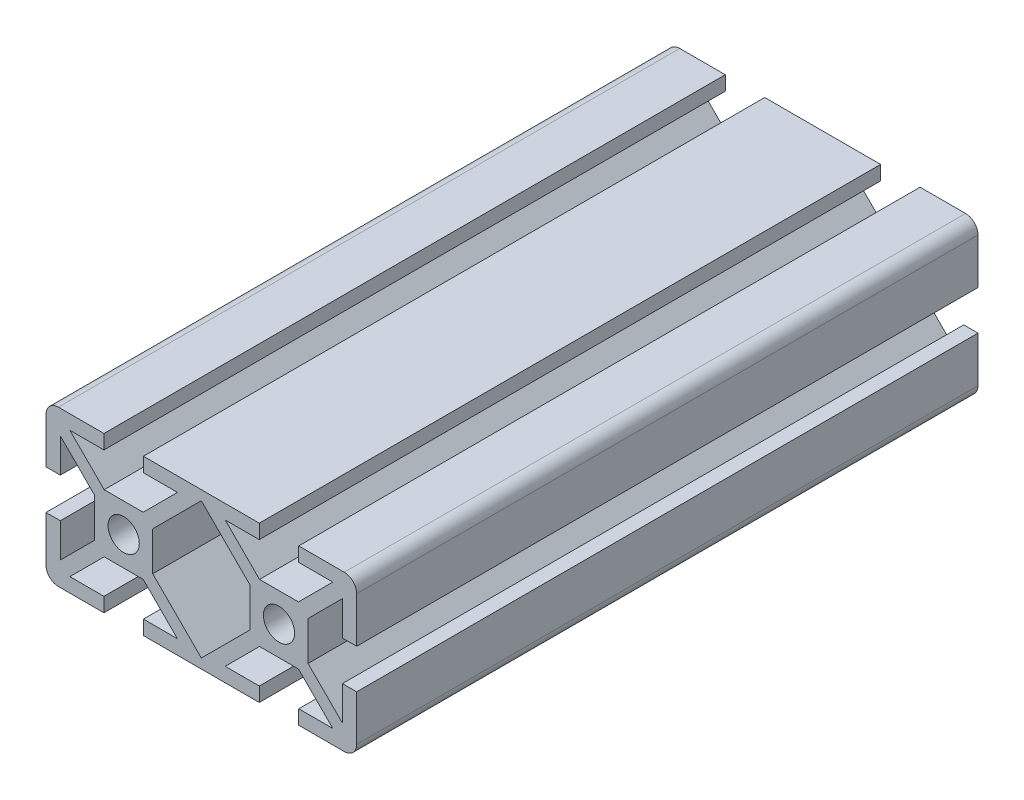
SolidWorks part; units mm, degrees
ref_plane "Front"
ref_plane "Top" through (0, 0, 0) normal (0, 1, 0) x (1, 0, 0)
ref_plane "Right" through (0, 0, 0) normal (1, 0, 0) x (0, 0, -1)
sketch "Sketch1" plane through (0, 0, 0) normal (0, 0, 1) x (1, 0, 0)
  line L0 (-12.7, 0) -> (-12.7, 36.1419) construction
  line L1 (-12.7, 0) -> (-38.1248, 0) construction
  line L2 (-17.4498, 0) -> (-17.4498, 3.1872)
  line L3 (-17.4498, 3.1872) -> (-23.0632, 8.8006)
  line L4 (-23.0632, 3.2258) -> (-23.0632, 8.8006)
  line L5 (-23.368, 12.7) -> (-15.9258, 12.7)
  line L6 (-25.4, 3.2258) -> (-25.4, 10.668)
  line L7 (-12.7, 4.7498) -> (-15.8872, 4.7498)
  line L8 (-15.8872, 4.7498) -> (-21.5006, 10.3632)
  line L9 (-21.5006, 10.3632) -> (-15.9258, 10.3632)
  line L10 (-9.5128, 4.7498) -> (-3.8994, 10.3632)
  line L11 (-3.8994, 10.3632) -> (-9.4742, 10.3632)
  line L12 (-15.9258, 12.7) -> (-15.9258, 10.3632)
  line L13 (9.4742, 12.7) -> (-9.4742, 12.7)
  line L14 (7.9502, 3.1872) -> (0, 11.1374)
  line L15 (-7.9502, 3.1872) -> (0, 11.1374)
  line L16 (-12.7, 4.7498) -> (-9.5128, 4.7498)
  line L17 (-7.9502, 3.1872) -> (-7.9502, 0)
  line L18 (-12.7, -4.7498) -> (-9.5128, -4.7498)
  line L19 (-7.9502, -3.1872) -> (0, -11.1374)
  line L20 (9.5128, 4.7498) -> (3.8994, 10.3632)
  line L21 (-9.5128, -4.7498) -> (-3.8994, -10.3632)
  line L22 (3.8994, 10.3632) -> (9.4742, 10.3632)
  line L23 (-3.8994, -10.3632) -> (-9.4742, -10.3632)
  line L24 (-9.4742, -12.7) -> (-9.4742, -10.3632)
  line L25 (-23.0632, -3.2258) -> (-25.4, -3.2258)
  line L26 (-23.0632, -3.2258) -> (-23.0632, -8.8006)
  line L27 (-12.7, -4.7498) -> (-15.8872, -4.7498)
  line L28 (-25.4, -3.2258) -> (-25.4, -10.668)
  line L29 (-23.368, -12.7) -> (-15.9258, -12.7)
  line L30 (-17.4498, -3.1872) -> (-23.0632, -8.8006)
  line L31 (-15.8872, -4.7498) -> (-21.5006, -10.3632)
  line L32 (-7.9502, 0) -> (-7.9502, -3.1872)
  line L33 (-17.4498, 0) -> (-17.4498, -3.1872)
  line L34 (0, 23.5779) -> (0, -24.9502) construction
  line L35 (9.4742, 12.7) -> (9.4742, 10.3632)
  line L36 (7.9502, 0) -> (7.9502, -3.1872)
  line L37 (7.9502, 3.1872) -> (7.9502, 0)
  line L38 (23.0632, 3.2258) -> (25.4, 3.2258)
  line L39 (15.9258, 12.7) -> (15.9258, 10.3632)
  line L40 (21.5006, 10.3632) -> (15.9258, 10.3632)
  line L41 (15.8872, 4.7498) -> (21.5006, 10.3632)
  line L42 (17.4498, 0) -> (17.4498, -3.1872)
  line L43 (25.4, 3.2258) -> (25.4, 10.668)
  line L44 (23.368, 12.7) -> (15.9258, 12.7)
  line L45 (23.0632, 3.2258) -> (23.0632, 8.8006)
  line L46 (17.4498, 3.1872) -> (23.0632, 8.8006)
  line L47 (12.7, -4.7498) -> (15.8872, -4.7498)
  line L48 (15.9258, -12.7) -> (15.9258, -10.3632)
  line L49 (21.5006, -10.3632) -> (15.9258, -10.3632)
  line L50 (12.7, -4.7498) -> (9.5128, -4.7498)
  line L51 (15.8872, 4.7498) -> (9.5128, 4.7498)
  line L52 (15.8872, -4.7498) -> (21.5006, -10.3632)
  line L53 (17.4498, -3.1872) -> (23.0632, -8.8006)
  line L54 (23.368, -12.7) -> (15.9258, -12.7)
  line L55 (25.4, -3.2258) -> (25.4, -10.668)
  line L56 (23.0632, -3.2258) -> (23.0632, -8.8006)
  line L57 (23.0632, -3.2258) -> (25.4, -3.2258)
  line L58 (9.4742, -12.7) -> (9.4742, -10.3632)
  line L59 (17.4498, 0) -> (17.4498, 3.1872)
  line L60 (-23.0632, 3.2258) -> (-25.4, 3.2258)
  line L61 (-9.4742, 12.7) -> (-9.4742, 10.3632)
  line L62 (-21.5006, -10.3632) -> (-15.9258, -10.3632)
  line L63 (-15.9258, -12.7) -> (-15.9258, -10.3632)
  line L64 (9.4742, -12.7) -> (-9.4742, -12.7)
  line L65 (3.8994, -10.3632) -> (9.4742, -10.3632)
  line L66 (9.5128, -4.7498) -> (3.8994, -10.3632)
  line L67 (7.9502, -3.1872) -> (0, -11.1374)
  arc A0 (-23.368, 12.7) -> (-25.4, 10.668) centre (-23.368, 10.668) ccw
  arc A1 (23.368, 12.7) -> (25.4, 10.668) centre (23.368, 10.668) cw
  arc A2 (23.368, -12.7) -> (25.4, -10.668) centre (23.368, -10.668) ccw
  arc A19 (-23.368, -12.7) -> (-25.4, -10.668) centre (-23.368, -10.668) cw
  circle A20 centre (-12.7, 0) radius 2.5527
  circle A23 centre (12.7, 0) radius 2.5527
  point P34 (0, 12.7)
  point P51 (0, -12.7)
  dimension "D2" = 12.7
  dimension "D5" = 2.2098
  dimension "D6" = 7.9502
  dimension "D4" = 9.4742
  dimension "D11" = 5.1054
  dimension "D12" = 12.7
  dimension "D3" = 2.032
  dimension "D1" = 12.7
  dimension "D7" = 7.9502
  dimension "D8" = 45
  dimension "D9" = 5.6134
  dimension "D10" = 5.6134
extrude "FinalCut" add sketch "Sketch1" against normal blind 101.6
ref_plane "A" through (0, 0, 0) normal (0, 0, 1) x (1, 0, 0)
ref_plane "B" through (0, 0, -101.6) normal (0, 0, -1) x (-1, 0, 0)
ref_plane "Y+" through (0, 12.7, 0) normal (0, 1, 0) x (-1, 0, 0)
ref_plane "X+" through (25.4, 0, 0) normal (1, 0, 0) x (0, 0, -1)
ref_plane "Y-" through (0, -12.7, 0) normal (0, -1, 0) x (1, 0, 0)
ref_plane "X-" through (-25.4, 0, 0) normal (-1, 0, 0) x (0, 0, 1)
ref_plane "Slot-3-6-" through (0, 0, 0) normal (0, 1, 0) x (0, 0, -1)
ref_plane "Slot-1-5-" through (-12.7, 0, 0) normal (1, 0, 0) x (0, 1, 0)
ref_plane "Slot-2-4-" through (12.7, 0, 0) normal (1, 0, 0) x (0, 1, 0)
sketch "Sketch3" plane through (0, 12.7, 0) normal (0, 1, 0) x (-1, 0, 0)
  line L0 (12.7, 0) -> (12.7, -31.4571) construction
  line L1 (9.5128, 0) -> (15.8872, 0) construction
  line L2 (15.9258, 0) -> (23.368, 0) construction
  circle A0 centre (12.7, -10.3124) radius 7.1501
  dimension "D2" = 14.3002
  dimension "D1" = 12.7
  dimension "D3" = 10.3124
extrude "AFA1" [suppressed] cut sketch "Sketch3" against normal blind 10.668
sketch "Sketch2" plane through (0, 12.7, 0) normal (0, 1, 0) x (-1, 0, 0)
  line L0 (-12.7, 0.1154) -> (-12.7, -30.7514) construction
  line L2 (-15.8872, 0) -> (-9.5128, 0) construction
  circle A0 centre (-12.7, -10.3124) radius 7.1501
  dimension "D2" = 14.3002
  dimension "D1" = 12.7
  dimension "D3" = 10.3124
extrude "AFA2" [suppressed] cut sketch "Sketch2" against normal blind 10.668
sketch "Sketch4" plane through (25.4, 0, 0) normal (1, 0, 0) x (0, 0, -1)
  line L0 (0, 0) -> (26.9656, 0) construction
  line L1 (0, -3.1872) -> (0, 3.1872) construction
  circle A0 centre (10.3124, 0) radius 7.1501
  dimension "D1" = 14.3002
  dimension "D2" = 10.3124
extrude "AFA3" [suppressed] cut sketch "Sketch4" against normal blind 10.668
sketch "Sketch5" plane through (0, -12.7, 0) normal (0, -1, 0) x (1, 0, 0)
  line L0 (12.7, 0) -> (12.7, -32.6419) construction
  line L1 (9.5128, 0) -> (15.8872, 0) construction
  circle A0 centre (12.7, -10.3124) radius 7.1501
  dimension "D2" = 14.3002
  dimension "D1" = 12.7
  dimension "D3" = 10.3124
extrude "AFA4" [suppressed] cut sketch "Sketch5" against normal blind 10.668
sketch "Sketch6" plane through (0, -12.7, 0) normal (0, -1, 0) x (1, 0, 0)
  line L0 (-12.7, 0) -> (-12.7, -32.1497) construction
  line L1 (-15.8872, 0) -> (-9.5128, 0) construction
  line L2 (-9.4742, 0) -> (9.4742, 0) construction
  circle A0 centre (-12.7, -10.3124) radius 7.1501
  dimension "D2" = 14.3002
  dimension "D1" = 12.7
  dimension "D3" = 10.3124
extrude "AFA5" [suppressed] cut sketch "Sketch6" against normal blind 10.668
sketch "Sketch7" plane through (-25.4, 0, 0) normal (-1, 0, 0) x (0, 0, 1)
  line L0 (0, 0) -> (-27.1523, 0) construction
  line L1 (0, 3.1872) -> (0, -3.1872) construction
  circle A0 centre (-10.3124, 0) radius 7.1501
  dimension "D1" = 14.3002
  dimension "D2" = 10.3124
extrude "AFA6" [suppressed] cut sketch "Sketch7" against normal blind 10.668
sketch "Sketch8" plane through (0, 12.7, 0) normal (0, 1, 0) x (-1, 0, 0)
  line L0 (12.7, -101.6) -> (12.7, 6.9228) construction
  line L1 (9.5128, -101.6) -> (15.8872, -101.6) construction
  circle A0 centre (12.7, -91.2876) radius 7.1501
  dimension "D1" = 14.3002
  dimension "D2" = 10.3124
  dimension "D3" = 12.7
extrude "AFB1" [suppressed] cut sketch "Sketch8" against normal blind 10.668
sketch "Sketch9" plane through (0, 12.7, 0) normal (0, 1, 0) x (-1, 0, 0)
  line L0 (-12.7, -17.9733) -> (-12.7, 12.1535) construction
  line L1 (-15.8872, -101.6) -> (-9.5128, -101.6) construction
  circle A0 centre (-12.7, -91.2876) radius 7.1501
  dimension "D1" = 14.3002
  dimension "D2" = 10.3124
  dimension "D3" = 12.7
extrude "AFB2" [suppressed] cut sketch "Sketch9" against normal blind 10.668
sketch "Sketch10" plane through (25.4, 0, 0) normal (1, 0, 0) x (0, 0, -1)
  line L0 (0, 0) -> (101.6, 0) construction
  line L1 (101.6, -3.1872) -> (101.6, 3.1872) construction
  circle A0 centre (91.2876, 0) radius 7.1501
  dimension "D1" = 14.3002
  dimension "D2" = 10.3124
extrude "AFB3" [suppressed] cut sketch "Sketch10" against normal blind 10.668
sketch "Sketch11" plane through (0, -12.7, 0) normal (0, -1, 0) x (1, 0, 0)
  line L0 (12.7, 0) -> (12.7, -101.6) construction
  line L1 (9.5128, 0) -> (15.8872, 0) construction
  line L2 (9.5128, -101.6) -> (15.8872, -101.6) construction
  line L3 (-9.4742, -101.6) -> (9.4742, -101.6) construction
  circle A0 centre (12.7, -91.2876) radius 7.1501
  dimension "D2" = 14.3002
  dimension "D1" = 12.7
  dimension "D3" = 10.3124
extrude "AFB4" [suppressed] cut sketch "Sketch11" against normal blind 10.668
sketch "Sketch12" plane through (0, -12.7, 0) normal (0, -1, 0) x (1, 0, 0)
  line L0 (-12.7, -101.6) -> (-12.7, 0) construction
  line L1 (-15.8872, -101.6) -> (-9.5128, -101.6) construction
  line L2 (-15.8872, 0) -> (-9.5128, 0) construction
  line L3 (-9.4742, -101.6) -> (9.4742, -101.6) construction
  circle A0 centre (-12.7, -91.2876) radius 7.1501
  dimension "D2" = 14.3002
  dimension "D1" = 12.7
  dimension "D3" = 10.3124
extrude "AFB5" [suppressed] cut sketch "Sketch12" against normal blind 10.668
sketch "Sketch13" plane through (-25.4, 0, 0) normal (-1, 0, 0) x (0, 0, 1)
  line L0 (0, 0) -> (-101.6, 0) construction
  line L1 (-101.6, 3.1872) -> (-101.6, -3.1872) construction
  line L2 (-101.6, -3.2258) -> (-101.6, -10.668) construction
  circle A0 centre (-91.2876, 0) radius 7.1501
  dimension "D1" = 14.3002
  dimension "D2" = 10.3124
extrude "AFB6" [suppressed] cut sketch "Sketch13" against normal blind 10.668
sketch "Sketch14" plane through (0, 0, -101.6) normal (0, 0, -1) x (-1, 0, 0)
  point P0 (0, 0)
sketch "Sketch15" plane through (0, 0, 0) normal (0, 0, 1) x (1, 0, 0)
  circle A0 centre (-12.7, 0) radius 3.302
  circle A1 centre (12.7, 0) radius 3.302
  dimension "D1" = 6.604
extrude "TPA660025" [suppressed] cut sketch "Sketch15" against normal blind 19.05
sketch "Sketch16" plane through (0, 0, -101.6) normal (0, 0, -1) x (-1, 0, 0)
  circle A0 centre (12.7, 0) radius 3.302
  circle A1 centre (-12.7, 0) radius 3.302
  dimension "D1" = 6.604
extrude "TPB660025" [suppressed] cut sketch "Sketch16" against normal blind 19.05
sketch "Sketch17" plane through (0, 0, 0) normal (0, 0, 1) x (1, 0, 0)
  circle A0 centre (-12.7, 0) radius 3.175
  circle A1 centre (12.7, 0) radius 3.175
  dimension "D1" = 6.35
extrude "TPA660026" [suppressed] cut sketch "Sketch17" against normal blind 25.4
sketch "Sketch18" plane through (0, 0, -101.6) normal (0, 0, -1) x (-1, 0, 0)
  circle A0 centre (12.7, 0) radius 3.175
  circle A1 centre (-12.7, 0) radius 3.175
  dimension "D1" = 6.35
extrude "TPB660026" [suppressed] cut sketch "Sketch18" against normal blind 25.4
sketch "Sketch19" plane through (0, 0, 0) normal (1, 0, 0) x (0, 0, -1)
  line L0 (0, 12.7) -> (25.4, -12.7)
  line L1 (101.6, 12.7) -> (0, 12.7) construction
  line L2 (101.6, -12.7) -> (0, -12.7) construction
  dimension "D1" = 45
extrude "MITA1" [suppressed] cut sketch "Sketch19" against normal through all and the other way through all flip side to cut
ref_plane "AMITA1" [suppressed] through (0, 6.35, -6.35) normal (0, 0.7071, -0.7071) x (-1, 0, 0)
ref_plane "AMIT0FFA1" [suppressed] through (0, 10.8401, -10.8401) normal (0, 0.7071, -0.7071) x (-1, 0, 0)
sketch "Sketch23" [suppressed] plane through (0, 10.8401, -10.8401) normal (0, 0.7071, -0.7071) x (-1, 0, 0)
  line L0 (-9.4742, 8.9803) -> (9.4742, 8.9803) construction
  circle A0 centre (-12.7, -8.9775) radius 7.9375
  circle A1 centre (12.7, -8.9775) radius 7.9375
  dimension "D1" = 25.4
  dimension "D2" = 15.875
  dimension "D3" = 12.7
  dimension "D4" = 17.9578
extrude "MITCBA1" [suppressed] cut sketch "Sketch23" along normal through all
sketch "Sketch24" [suppressed] plane through (0, 10.8401, -10.8401) normal (0, 0.7071, -0.7071) x (-1, 0, 0)
  line L1 (-9.4742, 8.9803) -> (9.4742, 8.9803) construction
  circle A0 centre (-12.7, -8.9775) radius 3.2639
  circle A1 centre (12.7, -8.9775) radius 3.2639
  dimension "D1" = 6.5278
  dimension "D2" = 25.4
  dimension "D3" = 12.7
  dimension "D4" = 17.9578
extrude "MITDRA1" [suppressed] cut sketch "Sketch24" against normal through all
sketch "Sketch25" [suppressed] plane through (0, 10.8401, -10.8401) normal (0, 0.7071, -0.7071) x (-1, 0, 0)
  line L0 (-20.6375, -8.9775) -> (-20.6375, 8.9803)
  line L1 (-4.7625, -8.9775) -> (-4.7625, 8.9803)
  line L2 (-4.7625, 8.9803) -> (-20.6375, 8.9803)
  line L3 (4.7625, 8.9803) -> (4.7625, -8.9775)
  line L4 (20.6375, -8.9775) -> (20.6375, 8.9803)
  line L5 (20.6375, 8.9803) -> (4.7625, 8.9803)
  line L6 (-9.4742, 8.9803) -> (9.4742, 8.9803) construction
  arc A0 (-20.6375, -8.9775) -> (-4.7625, -8.9775) centre (-12.7, -8.9775) ccw
  arc A1 (4.7625, -8.9775) -> (20.6375, -8.9775) centre (12.7, -8.9775) ccw
  dimension "D1" = 7.9375
  dimension "D3" = 25.4
  dimension "D4" = 12.7
  dimension "D2" = 17.9578
extrude "MITEBA1" [suppressed] cut sketch "Sketch25" along normal through all
sketch "Sketch26" [suppressed] plane through (0, 10.8401, -10.8401) normal (0, 0.7071, -0.7071) x (-1, 0, 0)
  line L0 (-15.9639, 8.9803) -> (-9.4361, 8.9803)
  line L1 (-9.4361, 8.9803) -> (-9.4361, -8.9775)
  line L2 (-15.9639, -8.9775) -> (-15.9639, 8.9803)
  line L3 (9.4361, 8.9803) -> (9.4361, -8.9775)
  line L4 (15.9639, -8.9775) -> (15.9639, 8.9803)
  line L5 (15.9639, 8.9803) -> (9.4361, 8.9803)
  line L6 (-9.4742, 8.9803) -> (9.4742, 8.9803) construction
  arc A0 (-9.4361, -8.9775) -> (-15.9639, -8.9775) centre (-12.7, -8.9775) cw
  arc A1 (9.4361, -8.9775) -> (15.9639, -8.9775) centre (12.7, -8.9775) ccw
  dimension "D1" = 3.2639
  dimension "D2" = 17.9578
  dimension "D3" = 25.4
  dimension "D4" = 12.7
extrude "MITEDA1" [suppressed] cut sketch "Sketch26" against normal through all
sketch "Sketch20" plane through (0, 0, 0) normal (1, 0, 0) x (0, 0, -1)
  line L0 (101.6, 12.7) -> (76.2, -12.7)
  line L1 (101.6, 12.7) -> (0, 12.7) construction
  line L2 (101.6, -12.7) -> (0, -12.7) construction
  dimension "D1" = 45
extrude "MITB1" [suppressed] cut sketch "Sketch20" against normal through all and the other way through all
ref_plane "AMITB1" [suppressed] through (0, -44.45, -44.45) normal (0, 0.7071, 0.7071) x (1, 0, 0)
ref_plane "AMITOFFB1" [suppressed] through (0, -39.9599, -39.9599) normal (0, 0.7071, 0.7071) x (1, 0, 0)
sketch "Sketch27" [suppressed] plane through (0, -39.9599, -39.9599) normal (0, 0.7071, 0.7071) x (1, 0, 0)
  line L1 (9.4742, 80.8223) -> (-9.4742, 80.8223) construction
  circle A0 centre (-12.7, 62.8645) radius 7.9375
  circle A1 centre (12.7, 62.8645) radius 7.9375
  dimension "D1" = 15.875
  dimension "D2" = 25.4
  dimension "D3" = 12.7
  dimension "D4" = 17.9578
extrude "MITCBB1" [suppressed] cut sketch "Sketch27" along normal through all
sketch "Sketch28" [suppressed] plane through (0, -39.9599, -39.9599) normal (0, 0.7071, 0.7071) x (1, 0, 0)
  line L0 (9.4742, 80.8223) -> (-9.4742, 80.8223) construction
  circle A0 centre (-12.7, 62.8645) radius 3.2639
  circle A1 centre (12.7, 62.8645) radius 3.2639
  dimension "D1" = 25.4
  dimension "D2" = 12.7
  dimension "D3" = 6.5278
  dimension "D4" = 17.9578
extrude "MITDRB1" [suppressed] cut sketch "Sketch28" against normal through all
sketch "Sketch29" [suppressed] plane through (0, -39.9599, -39.9599) normal (0, 0.7071, 0.7071) x (1, 0, 0)
  line L0 (-20.6375, 80.8223) -> (-20.6375, 62.8645)
  line L1 (-4.7625, 62.8645) -> (-4.7625, 80.8223)
  line L2 (-4.7625, 80.8223) -> (-20.6375, 80.8223)
  line L3 (4.7625, 80.8223) -> (4.7625, 62.8645)
  line L4 (20.6375, 62.8645) -> (20.6375, 80.8223)
  line L5 (20.6375, 80.8223) -> (4.7625, 80.8223)
  line L8 (9.4742, 80.8223) -> (-9.4742, 80.8223) construction
  arc A0 (-20.6375, 62.8645) -> (-4.7625, 62.8645) centre (-12.7, 62.8645) ccw
  arc A1 (4.7625, 62.8645) -> (20.6375, 62.8645) centre (12.7, 62.8645) ccw
  dimension "D1" = 25.4
  dimension "D2" = 12.7
  dimension "D3" = 7.9375
  dimension "D4" = 17.9578
extrude "MITEBB1" [suppressed] cut sketch "Sketch29" along normal through all
sketch "Sketch30" [suppressed] plane through (0, -39.9599, -39.9599) normal (0, 0.7071, 0.7071) x (1, 0, 0)
  line L0 (-15.9639, 80.8223) -> (-15.9639, 62.8645)
  line L1 (-9.4361, 62.8645) -> (-9.4361, 80.8223)
  line L2 (-9.4361, 80.8223) -> (-15.9639, 80.8223)
  line L3 (9.4361, 80.8223) -> (9.4361, 62.8645)
  line L4 (15.9639, 62.8645) -> (15.9639, 80.8223)
  line L5 (15.9639, 80.8223) -> (9.4361, 80.8223)
  line L6 (9.4742, 80.8223) -> (-9.4742, 80.8223) construction
  arc A0 (-15.9639, 62.8645) -> (-9.4361, 62.8645) centre (-12.7, 62.8645) ccw
  arc A1 (9.4361, 62.8645) -> (15.9639, 62.8645) centre (12.7, 62.8645) ccw
  dimension "D1" = 17.9578
  dimension "D2" = 3.2639
  dimension "D3" = 25.4
  dimension "D4" = 12.7
extrude "MITEDB1" [suppressed] cut sketch "Sketch30" against normal through all
sketch "Sketch21" plane through (0, 0, 0) normal (1, 0, 0) x (0, 0, -1)
  line L0 (0, -12.7) -> (25.4, 12.7)
  line L1 (101.6, -12.7) -> (0, -12.7) construction
  line L2 (101.6, 12.7) -> (0, 12.7) construction
  dimension "D1" = 45
extrude "MITA4" [suppressed] cut sketch "Sketch21" against normal through all and the other way through all
ref_plane "AMITA4" [suppressed] through (0, -6.35, -6.35) normal (0, -0.7071, -0.7071) x (-1, 0, 0)
ref_plane "AMITOFFA4" [suppressed] through (0, -10.8401, -10.8401) normal (0, -0.7071, -0.7071) x (-1, 0, 0)
sketch "Sketch31" [suppressed] plane through (0, -10.8401, -10.8401) normal (0, -0.7071, -0.7071) x (-1, 0, 0)
  line L0 (9.4742, -8.9803) -> (-9.4742, -8.9803) construction
  circle A0 centre (-12.7, 8.9775) radius 7.9375
  circle A1 centre (12.7, 8.9775) radius 7.9375
  dimension "D1" = 15.875
  dimension "D2" = 12.7
  dimension "D3" = 25.4
  dimension "D4" = 17.9578
extrude "MITCBA4" [suppressed] cut sketch "Sketch31" along normal through all
sketch "Sketch32" [suppressed] plane through (0, -10.8401, -10.8401) normal (0, -0.7071, -0.7071) x (-1, 0, 0)
  line L0 (9.4742, -8.9803) -> (-9.4742, -8.9803) construction
  circle A0 centre (-12.7, 8.9775) radius 3.2639
  circle A1 centre (12.7, 8.9775) radius 3.2639
  dimension "D1" = 6.5278
  dimension "D2" = 17.9578
  dimension "D3" = 25.4
  dimension "D4" = 12.7
extrude "MITDRA4" [suppressed] cut sketch "Sketch32" against normal through all
sketch "Sketch33" [suppressed] plane through (0, -10.8401, -10.8401) normal (0, -0.7071, -0.7071) x (-1, 0, 0)
  line L0 (-20.6375, -8.9803) -> (-4.7625, -8.9803)
  line L1 (-4.7625, -8.9803) -> (-4.7625, 8.9775)
  line L2 (-20.6375, 8.9775) -> (-20.6375, -8.9803)
  line L3 (4.7625, -8.9803) -> (4.7625, 8.9775)
  line L4 (20.6375, 8.9775) -> (20.6375, -8.9803)
  line L5 (20.6375, -8.9803) -> (4.7625, -8.9803)
  line L6 (9.4742, -8.9803) -> (-9.4742, -8.9803) construction
  arc A0 (-4.7625, 8.9775) -> (-20.6375, 8.9775) centre (-12.7, 8.9775) ccw
  arc A1 (4.7625, 8.9775) -> (20.6375, 8.9775) centre (12.7, 8.9775) cw
  dimension "D1" = 7.9375
  dimension "D3" = 25.4
  dimension "D4" = 12.7
  dimension "D2" = 17.9578
extrude "MITEBA4" [suppressed] cut sketch "Sketch33" along normal through all
sketch "Sketch34" [suppressed] plane through (0, -10.8401, -10.8401) normal (0, -0.7071, -0.7071) x (-1, 0, 0)
  line L0 (-15.9639, -8.9803) -> (-15.9639, 8.9775)
  line L1 (-9.4361, 8.9775) -> (-9.4361, -8.9803)
  line L2 (-9.4361, -8.9803) -> (-15.9639, -8.9803)
  line L3 (9.4361, -8.9803) -> (9.4361, 8.9775)
  line L4 (15.9639, 8.9775) -> (15.9639, -8.9803)
  line L5 (15.9639, -8.9803) -> (9.4361, -8.9803)
  line L6 (9.4742, -8.9803) -> (-9.4742, -8.9803) construction
  arc A0 (-15.9639, 8.9775) -> (-9.4361, 8.9775) centre (-12.7, 8.9775) cw
  arc A1 (9.4361, 8.9775) -> (15.9639, 8.9775) centre (12.7, 8.9775) cw
  dimension "D1" = 3.2639
  dimension "D3" = 25.4
  dimension "D4" = 12.7
  dimension "D2" = 17.9578
extrude "MITEDA4" [suppressed] cut sketch "Sketch34" against normal through all
sketch "Sketch22" plane through (0, 0, 0) normal (1, 0, 0) x (0, 0, -1)
  line L0 (76.2, 12.7) -> (101.6, -12.7)
  line L1 (101.6, 12.7) -> (0, 12.7) construction
  line L2 (101.6, -12.7) -> (0, -12.7) construction
  dimension "D1" = 45
extrude "MITB4" [suppressed] cut sketch "Sketch22" against normal through all and the other way through all
ref_plane "AMITB4" [suppressed] through (0, 44.45, -44.45) normal (0, -0.7071, 0.7071) x (1, 0, 0)
ref_plane "AMITOFFB4" [suppressed] through (0, 39.9599, -39.9599) normal (0, -0.7071, 0.7071) x (1, 0, 0)
sketch "Sketch35" [suppressed] plane through (0, 39.9599, -39.9599) normal (0, -0.7071, 0.7071) x (1, 0, 0)
  line L0 (-9.4742, -80.8223) -> (9.4742, -80.8223) construction
  circle A0 centre (12.7, -62.8645) radius 7.9375
  circle A1 centre (-12.7, -62.8645) radius 7.9375
  dimension "D1" = 15.875
  dimension "D2" = 17.9578
  dimension "D3" = 25.4
  dimension "D4" = 12.7
extrude "MITCBB4" [suppressed] cut sketch "Sketch35" along normal through all
sketch "Sketch36" [suppressed] plane through (0, 39.9599, -39.9599) normal (0, -0.7071, 0.7071) x (1, 0, 0)
  line L0 (-9.4742, -80.8223) -> (9.4742, -80.8223) construction
  circle A0 centre (12.7, -62.8645) radius 3.2639
  circle A1 centre (-12.7, -62.8645) radius 3.2639
  dimension "D1" = 25.4
  dimension "D2" = 6.5278
  dimension "D3" = 12.7
  dimension "D4" = 17.9578
extrude "MITDRB4" [suppressed] cut sketch "Sketch36" against normal through all
sketch "Sketch37" [suppressed] plane through (0, 39.9599, -39.9599) normal (0, -0.7071, 0.7071) x (1, 0, 0)
  line L0 (-20.6248, -80.8223) -> (-20.6248, -62.8645)
  line L1 (-4.7752, -62.8645) -> (-4.7752, -80.8223)
  line L2 (-4.7752, -80.8223) -> (-20.6248, -80.8223)
  line L3 (4.7752, -80.8223) -> (4.7752, -62.8645)
  line L4 (20.6248, -62.8645) -> (20.6248, -80.8223)
  line L5 (20.6248, -80.8223) -> (4.7752, -80.8223)
  line L6 (-9.4742, -80.8223) -> (9.4742, -80.8223) construction
  arc A0 (-20.6248, -62.8645) -> (-4.7752, -62.8645) centre (-12.7, -62.8645) cw
  arc A1 (4.7752, -62.8645) -> (20.6248, -62.8645) centre (12.7, -62.8645) cw
  dimension "D1" = 7.9248
  dimension "D2" = 25.4
  dimension "D3" = 17.9578
  dimension "D4" = 12.7
extrude "MITEBB4" [suppressed] cut sketch "Sketch37" along normal through all
sketch "Sketch38" [suppressed] plane through (0, 39.9599, -39.9599) normal (0, -0.7071, 0.7071) x (1, 0, 0)
  line L0 (-15.9639, -80.8223) -> (-15.9639, -62.8645)
  line L1 (-9.4361, -62.8645) -> (-9.4361, -80.8223)
  line L2 (-9.4361, -80.8223) -> (-15.9639, -80.8223)
  line L3 (9.4361, -80.8223) -> (9.4361, -62.8645)
  line L4 (15.9639, -62.8645) -> (15.9639, -80.8223)
  line L5 (15.9639, -80.8223) -> (9.4361, -80.8223)
  line L6 (-9.4742, -80.8223) -> (9.4742, -80.8223) construction
  arc A0 (-15.9639, -62.8645) -> (-9.4361, -62.8645) centre (-12.7, -62.8645) cw
  arc A1 (9.4361, -62.8645) -> (15.9639, -62.8645) centre (12.7, -62.8645) cw
  dimension "D1" = 25.4
  dimension "D2" = 12.7
  dimension "D3" = 3.2639
  dimension "D4" = 17.9578
extrude "MITEDB4" [suppressed] cut sketch "Sketch38" against normal through all
